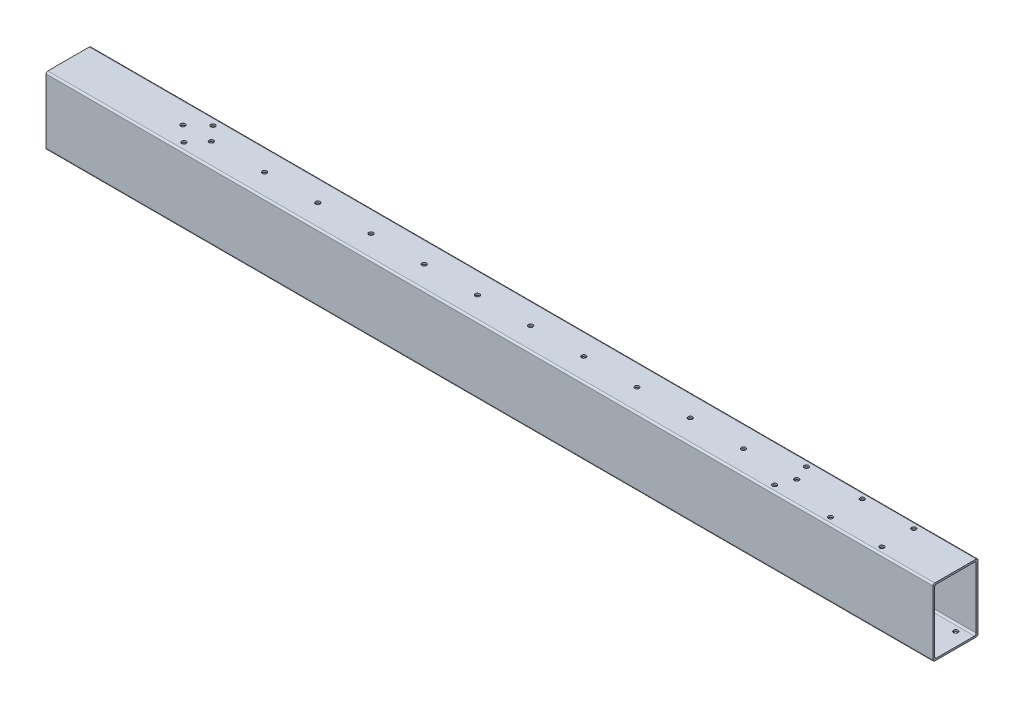
SolidWorks part; units mm, degrees
material "A500"
ref_plane "Alzado" through (0, 0, 0) normal (0, 0, 1) x (1, 0, 0)
ref_plane "Planta" through (0, 0, 0) normal (0, 1, 0) x (1, 0, 0)
ref_plane "Vista lateral" through (0, 0, 0) normal (1, 0, 0) x (0, 0, -1)
sketch "Sketch1" plane through (0, 0, 0) normal (1, 0, 0) x (0, 0, -1)
  line L1 (25.4, 38.1) -> (-25.4, 38.1)
  line L2 (25.4, 38.1) -> (25.4, -38.1)
  line L3 (25.4, -38.1) -> (-25.4, -38.1)
  line L4 (-25.4, 38.1) -> (-25.4, -38.1)
  line L5 (25.4, 38.1) -> (-25.4, -38.1) construction
  line L6 (25.4, -38.1) -> (-25.4, 38.1) construction
  point P0 (0, 0)
  dimension "D1" = 76.2
  dimension "D2" = 50.8
extrude "Boss-Extrude1" add sketch "Sketch1" against normal blind 1000
sketch "Sketch2" plane through (0, 0, 0) normal (1, 0, 0) x (0, 0, -1)
  line L0 (25.4, 38.1) -> (-25.4, 38.1) construction
  line L1 (23.4, 36.1) -> (-23.4, 36.1)
  line L2 (23.4, 36.1) -> (23.4, -36.1)
  line L3 (23.4, -36.1) -> (-23.4, -36.1)
  line L4 (-23.4, 36.1) -> (-23.4, -36.1)
  line L5 (23.4, 36.1) -> (-23.4, -36.1) construction
  line L6 (23.4, -36.1) -> (-23.4, 36.1) construction
  line L7 (25.4, -38.1) -> (25.4, 38.1) construction
  point P0 (0, 0)
  dimension "D1" = 2
  dimension "D2" = 2
extrude "Cut-Extrude1" cut sketch "Sketch2" against normal through all
fillet "Fillet2" radius 2 8 edges at (-500, -38.1, -25.4) (-500, -38.1, 25.4) (-500, 38.1, 25.4) (-500, 38.1, -25.4) (-500, -36.1, -23.4) (-500, 36.1, -23.4) (-500, -36.1, 23.4) (-500, 36.1, 23.4)
sketch "Croquis2" plane through (0, -38.1, 0) normal (0, -1, 0) x (1, 0, 0)
  line L0 (-76.2, 25.4) -> (-76.2, -25.4) construction
  line L1 (-1000, 25.4) -> (0, 25.4) construction
  line L2 (0, -25.4) -> (-1000, -25.4) construction
  line L3 (0, 23.4) -> (0, -23.4) construction
  line L4 (-76.2, 15.4) -> (0, 15.4) construction
  line L5 (-76.2, -15.4) -> (0, -15.4) construction
  line L6 (0, 0) -> (-76.2, 0) construction
  circle A0 centre (-61.2, 15.4) radius 2.5
  circle A1 centre (-38.1, 0) radius 2.5
  circle A2 centre (-61.2, -15.4) radius 2.5
  circle A3 centre (-15, -15.4) radius 2.5
  circle A4 centre (-15, 15.4) radius 2.5
  dimension "D8" = 5
  dimension "D9" = 5
  dimension "D10" = 5
  dimension "D11" = 5
  dimension "D12" = 5
  dimension "D1" = 76.2
  dimension "D2" = 10
  dimension "D3" = 10
  dimension "D4" = 15
  dimension "D5" = 15
  dimension "D6" = 15
  dimension "D7" = 15
extrude "Cortar-Extruir2" cut sketch "Croquis2" against normal blind 10
sketch "Croquis3" plane through (0, -38.1, 0) normal (0, -1, 0) x (1, 0, 0)
  line L0 (-923.8, 25.4) -> (-923.8, -25.4) construction
  line L1 (-1000, 25.4) -> (0, 25.4) construction
  line L2 (0, -25.4) -> (-1000, -25.4) construction
  line L3 (-1000, 23.4) -> (-1000, -23.4) construction
  line L4 (-923.8, 15.4) -> (-1000, 15.4) construction
  line L5 (-923.8, -15.4) -> (-1000, -15.4) construction
  line L6 (-923.8, 0) -> (-1000, 0) construction
  circle A0 centre (-985, 15.4) radius 2.5
  circle A1 centre (-938.8, 15.4) radius 2.5
  circle A2 centre (-961.9, 0) radius 2.5
  circle A3 centre (-985, -15.4) radius 2.5
  circle A4 centre (-938.8, -15.4) radius 2.5
  dimension "D8" = 5
  dimension "D9" = 5
  dimension "D10" = 5
  dimension "D11" = 5
  dimension "D12" = 5
  dimension "D1" = 76.2
  dimension "D2" = 10
  dimension "D3" = 10
  dimension "D4" = 15
  dimension "D5" = 15
  dimension "D6" = 15
  dimension "D7" = 15
extrude "Cortar-Extruir3" cut sketch "Croquis3" against normal blind 10
sketch "Croquis4" plane through (0, 38.1, 0) normal (0, 1, 0) x (1, 0, 0)
  line L0 (-882, 25.4) -> (-882, -25.4) construction
  line L1 (-1000, 25.4) -> (0, 25.4) construction
  line L2 (0, -25.4) -> (-1000, -25.4) construction
  line L3 (-1000, 23.4) -> (-1000, -23.4) construction
  line L4 (-853.5, 25.4) -> (-853.5, -25.4) construction
  line L5 (-853.5, -25.4) -> (-651.7775, -25.4) construction
  line L6 (-1000, -25.4) -> (0, -25.4) construction
  line L7 (-853.5, 0) -> (-882, 0) construction
  circle A0 centre (-853.5, 16.4) radius 2.5
  circle A1 centre (-853.5, -16.4) radius 2.5
  circle A3 centre (-871, 0) radius 2.5
  dimension "D6" = 5
  dimension "D7" = 5
  dimension "D8" = 5
  dimension "D1" = 118
  dimension "D2" = 28.5
  dimension "D3" = 11
  dimension "D4" = 16.4
  dimension "D5" = 16.4
extrude "Cortar-Extruir4" cut sketch "Croquis4" against normal blind 10
sketch "Croquis5" plane through (0, 38.1, 0) normal (0, 1, 0) x (1, 0, 0)
  line L0 (-34, 25.4) -> (-34, -25.4) construction
  line L1 (-1000, 25.4) -> (0, 25.4) construction
  line L2 (0, -25.4) -> (-1000, -25.4) construction
  line L3 (0, 23.4) -> (0, -23.4) construction
  line L4 (0, 17.9) -> (-186, 17.9) construction
  line L5 (-186, 17.9) -> (-186, -17.9) construction
  line L6 (-186, -17.9) -> (0, -17.9) construction
  circle A0 centre (-186, 17.9) radius 2.5
  circle A1 centre (-186, -17.9) radius 2.5
  circle A2 centre (-123, -17.9) radius 2.5
  circle A3 centre (-123, 17.9) radius 2.5
  circle A4 centre (-65, 17.9) radius 2.5
  circle A5 centre (-65, -17.9) radius 2.5
  dimension "D9" = 5
  dimension "D10" = 5
  dimension "D11" = 5
  dimension "D12" = 5
  dimension "D13" = 5
  dimension "D14" = 5
  dimension "D1" = 34
  dimension "D2" = 7.5
  dimension "D3" = 7.5
  dimension "D4" = 152
  dimension "D5" = 31
  dimension "D6" = 58
  dimension "D7" = 31
  dimension "D8" = 58
extrude "Cortar-Extruir5" cut sketch "Croquis5" against normal blind 10
sketch "Croquis6" plane through (0, 38.1, 0) normal (0, 1, 0) x (1, 0, 0)
  line L0 (0, 0) -> (-179, 0) construction
  circle A0 centre (-179, 0) radius 2.5
  dimension "D1" = 5
  dimension "D2" = 179
extrude "Cortar-Extruir6" cut sketch "Croquis6" against normal through all
pattern_linear "MatrizL1" count 12 spacing 60 along (-1, 0, 0) of "Cortar-Extruir6"
sketch "Croquis7" plane through (0, 0, -25.4) normal (0, 0, -1) x (-1, 0, 0)
  line L0 (0, -18.1) -> (1000, -18.1) construction
  line L1 (0, -36.1) -> (0, 36.1) construction
  line L2 (1000, -36.1) -> (1000, 36.1) construction
  line L3 (1000, -38.1) -> (0, -38.1) construction
  line L4 (0, 8.1) -> (1000, 8.1) construction
  line L5 (0, 38.1) -> (1000, 38.1) construction
  circle A0 centre (75, -18.1) radius 2.5
  circle A1 centre (355, -18.1) radius 2.5
  circle A2 centre (635, -18.1) radius 2.5
  circle A3 centre (915, -18.1) radius 2.5
  circle A5 centre (265, 8.1) radius 2.5
  circle A6 centre (830, 8.1) radius 2.5
  dimension "D3" = 5
  dimension "D7" = 5
  dimension "D8" = 5
  dimension "D9" = 5
  dimension "D11" = 5
  dimension "D12" = 5
  dimension "D1" = 75
  dimension "D2" = 20
  dimension "D4" = 280
  dimension "D5" = 280
  dimension "D6" = 280
  dimension "D10" = 30
  dimension "D13" = 265
  dimension "D14" = 170
extrude "Cortar-Extruir7" cut sketch "Croquis7" against normal blind 10
